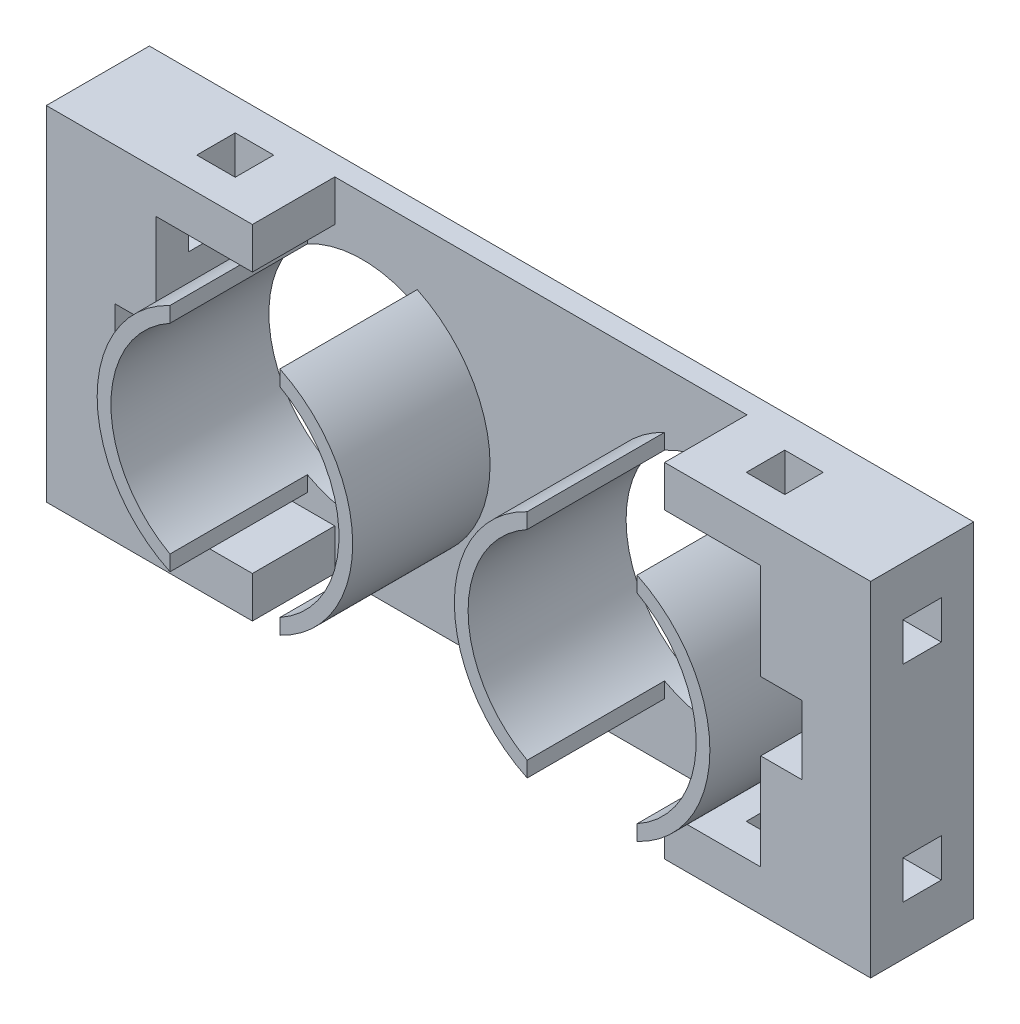
SolidWorks part; units mm, degrees
ref_plane "Plano frontal" through (0, 0, 0) normal (0, 0, 1) x (1, 0, 0)
ref_plane "Plano superior" through (0, 0, 0) normal (0, 1, 0) x (1, 0, 0)
ref_plane "Plano direito" through (0, 0, 0) normal (1, 0, 0) x (0, 0, -1)
sketch "Esboço1" plane through (0, 0, 0) normal (0, 0, 1) x (1, 0, 0)
  line L0 (-5, 0) -> (5, 0) construction
  line L1 (25, 0) -> (-25, 0) construction
  line L2 (0, 0) -> (0, -12.5) construction
  line L3 (25, -12.5) -> (-25, -12.5) construction
  line L4 (-21, 0) -> (-5, 0) construction
  line L5 (-25, -12.5) -> (-25, 12.5)
  line L6 (-25, 12.5) -> (25, 12.5)
  line L7 (0, 12.5) -> (0, 0) construction
  line L8 (20, -12.5) -> (-20, -12.5) construction
  line L12 (-15, -12.5) -> (15, -12.5)
  line L23 (21, 0) -> (5, 0) construction
  line L31 (25, -12.5) -> (25, 12.5)
  line L32 (-25, -12.5) -> (-15, -12.5)
  line L33 (15, -12.5) -> (25, -12.5)
  circle A0 centre (-13, 0) radius 8.3
  circle A1 centre (13, 0) radius 8.3
extrude "Ressalto-extrusão1" add sketch "Esboço1" along normal blind 1.5
sketch "Esboço2" plane through (0, 0, 1.5) normal (0, 0, 1) x (1, 0, 0)
  line L0 (-20, -12.5) -> (-25, -12.5)
  line L1 (0, -12.5) -> (0, 12.5) construction
  line L2 (20, -12.5) -> (-20, -12.5) construction
  line L3 (-25, -12.5) -> (25, -12.5) construction
  line L4 (22, -2.5) -> (22, -9.5)
  line L5 (-25, 12.5) -> (-25, -12.5) construction
  line L6 (-22, -9.5) -> (-15, -9.5)
  line L7 (-15, -9.5) -> (-15, -12.5)
  line L8 (-15, -12.5) -> (-20, -12.5)
  line L9 (-25, -12.5) -> (-25, -2.5)
  line L10 (-25, -2.5) -> (-22, -2.5)
  line L11 (-22, -2.5) -> (-22, -9.5)
  line L12 (25, -2.5) -> (22, -2.5)
  line L13 (25, -12.5) -> (25, -2.5)
  line L14 (15, -12.5) -> (20, -12.5)
  line L15 (25, 12.5) -> (-25, 12.5) construction
  line L16 (15, -9.5) -> (15, -12.5)
  line L17 (-25, 0) -> (25, 0) construction
  line L18 (25, -12.5) -> (25, 12.5) construction
  line L19 (22, -9.5) -> (15, -9.5)
  line L20 (20, -12.5) -> (25, -12.5)
  line L21 (20, 12.5) -> (-20, 12.5) construction
  line L22 (20, 12.5) -> (25, 12.5)
  line L23 (22, 9.5) -> (15, 9.5)
  line L24 (15, 9.5) -> (15, 12.5)
  line L25 (15, 12.5) -> (20, 12.5)
  line L26 (25, 12.5) -> (25, 2.5)
  line L27 (25, 2.5) -> (22, 2.5)
  line L28 (-22, 2.5) -> (-22, 9.5)
  line L29 (-25, 2.5) -> (-22, 2.5)
  line L30 (-25, 12.5) -> (-25, 2.5)
  line L31 (-15, 12.5) -> (-20, 12.5)
  line L32 (-15, 9.5) -> (-15, 12.5)
  line L33 (-22, 9.5) -> (-15, 9.5)
  line L34 (22, 2.5) -> (22, 9.5)
  line L35 (-20, 12.5) -> (-25, 12.5)
extrude "Ressalto-extrusão2" add sketch "Esboço2" along normal blind 6
sketch "Esboço3" plane through (0, -12.5, 0) normal (0, -1, 0) x (1, 0, 0)
  line L0 (-25, 3.75) -> (-15, 3.75) construction
  line L1 (-25, 7.5) -> (-25, 0) construction
  line L2 (-15, 7.5) -> (-15, 1.5) construction
  line L3 (-15, 3.75) -> (-20, 3.75) construction
  line L4 (-20, 3.75) -> (-20, 7.5) construction
  line L5 (-25, 7.5) -> (-15, 7.5) construction
  line L6 (0, 0) -> (0, 8.9122) construction
  line L7 (-21.4, 2.35) -> (-18.6, 2.35)
  line L8 (-21.4, 2.35) -> (-21.4, 5.15)
  line L9 (-21.4, 5.15) -> (-18.6, 5.15)
  line L10 (-18.6, 2.35) -> (-18.6, 5.15)
  line L11 (-21.4, 2.35) -> (-18.6, 5.15) construction
  line L12 (-21.4, 5.15) -> (-18.6, 2.35) construction
  line L13 (-25, 0) -> (25, 0) construction
  line L14 (21.4, 5.15) -> (18.6, 2.35) construction
  line L15 (21.4, 2.35) -> (18.6, 5.15) construction
  line L16 (18.6, 2.35) -> (18.6, 5.15)
  line L17 (21.4, 5.15) -> (18.6, 5.15)
  line L18 (21.4, 2.35) -> (21.4, 5.15)
  line L19 (21.4, 2.35) -> (18.6, 2.35)
extrude "Corte-extrusão1" cut sketch "Esboço3" against normal through all
sketch "Esboço4" plane through (-25, 0, 0) normal (-1, 0, 0) x (0, 0, 1)
  line L2 (3.75, 2.5) -> (3.75, 12.5) construction
  line L5 (3.75, -2.5) -> (3.75, -12.5) construction
  line L9 (0, 12.5) -> (7.5, 12.5) construction
  line L10 (5.15, 8.9) -> (2.35, 8.9)
  line L11 (5.15, 8.9) -> (5.15, 6.1)
  line L12 (5.15, 6.1) -> (2.35, 6.1)
  line L13 (2.35, 8.9) -> (2.35, 6.1)
  line L14 (5.15, 8.9) -> (2.35, 6.1) construction
  line L15 (5.15, 6.1) -> (2.35, 8.9) construction
  line L16 (5.15, -6.1) -> (2.35, -6.1)
  line L17 (5.15, -6.1) -> (5.15, -8.9)
  line L18 (5.15, -8.9) -> (2.35, -8.9)
  line L19 (2.35, -6.1) -> (2.35, -8.9)
  line L20 (5.15, -6.1) -> (2.35, -8.9) construction
  line L21 (5.15, -8.9) -> (2.35, -6.1) construction
  point P12 (3.75, 7.5)
  point P17 (3.75, -7.5)
  point P26 (3.75, 12.5)
extrude "Corte-extrusão2" cut sketch "Esboço4" against normal through all
sketch "Esboço6" plane through (0, 0, 0) normal (0, 0, -1) x (-1, 0, 0)
  line L0 (-25, 12.5) -> (-25, -12.5)
  line L1 (-30, -12.5) -> (-25, -12.5)
  line L2 (-30, -12.5) -> (-30, 12.5)
  line L3 (-30, 12.5) -> (-25, 12.5)
  line L4 (30, -12.5) -> (30, 12.5)
  line L5 (-30, -12.5) -> (30, 12.5) construction
  line L6 (-30, 12.5) -> (30, -12.5) construction
  line L7 (25, 12.5) -> (25, -12.5)
  line L8 (25, 12.5) -> (30, 12.5)
  line L9 (25, -12.5) -> (30, -12.5)
  point P0 (0, 0)
extrude "Ressalto-extrusão5" add sketch "Esboço6" against normal up to surface (7.5 mm away) up to face at (20.6667, -8.1667, 7.5)
sketch "Esboço7" plane through (30, 0, 0) normal (1, 0, 0) x (0, 0, -1)
  line L0 (-2.35, -6.1) -> (-5.15, -6.1) construction
  line L1 (-2.35, -8.9) -> (-2.35, -6.1) construction
  line L2 (-5.15, -8.9) -> (-2.35, -8.9) construction
  line L3 (-5.15, -6.1) -> (-5.15, -8.9) construction
  line L4 (-2.35, -6.1) -> (-5.15, -6.1)
  line L5 (-2.35, -8.9) -> (-2.35, -6.1)
  line L6 (-5.15, -8.9) -> (-2.35, -8.9)
  line L7 (-5.15, -6.1) -> (-5.15, -8.9)
  line L8 (-2.35, 6.1) -> (-2.35, 8.9) construction
  line L9 (-2.35, 8.9) -> (-5.15, 8.9) construction
  line L10 (-5.15, 8.9) -> (-5.15, 6.1) construction
  line L11 (-5.15, 6.1) -> (-2.35, 6.1) construction
  line L12 (-2.35, 6.1) -> (-2.35, 8.9)
  line L13 (-2.35, 8.9) -> (-5.15, 8.9)
  line L14 (-5.15, 8.9) -> (-5.15, 6.1)
  line L15 (-5.15, 6.1) -> (-2.35, 6.1)
extrude "Corte-extrusão3" cut sketch "Esboço7" against normal up to surface (60 mm away) up to face at (-30, 0, 3.75)
sketch "Esboço5" plane through (0, 0, 1.5) normal (0, 0, 1) x (1, 0, 0)
  line L0 (-9, -7.2726) -> (-9, -8.3958)
  line L1 (-17, -7.2726) -> (-17, -8.3958)
  line L2 (-17, 8.3958) -> (-17, 7.2726)
  line L3 (9, -7.2726) -> (9, -8.3958)
  line L4 (-9, 8.3958) -> (-9, 7.2726)
  line L8 (17, 8.3958) -> (17, 7.2726)
  line L10 (9, 8.3958) -> (9, 7.2726)
  line L13 (17, -7.2726) -> (17, -8.3958)
  circle A0 centre (-13, 0) radius 8.3 construction
  circle A1 centre (13, 0) radius 8.3 construction
  arc A2 (-17, 7.2726) -> (-17, -7.2726) centre (-13, 0) ccw
  arc A3 (17, -7.2726) -> (17, 7.2726) centre (13, 0) ccw
  arc A4 (-17, 8.3958) -> (-17, -8.3958) centre (-13, 0) ccw
  arc A5 (17, -8.3958) -> (17, 8.3958) centre (13, 0) ccw
  circle A6 centre (-13, 0) radius 8.3 construction
  circle A7 centre (-13, 0) radius 9.3 construction
  circle A8 centre (13, 0) radius 8.3 construction
  circle A9 centre (13, 0) radius 9.3 construction
  arc A12 (-9, -8.3958) -> (-9, 8.3958) centre (-13, 0) ccw
  arc A13 (-9, -7.2726) -> (-9, 7.2726) centre (-13, 0) ccw
  arc A14 (9, 7.2726) -> (9, -7.2726) centre (13, 0) ccw
  arc A15 (9, 8.3958) -> (9, -8.3958) centre (13, 0) ccw
  dimension "D1" = 1
  dimension "D2" = 1
extrude "Ressalto-extrusão3" add sketch "Esboço5" along normal blind 10
